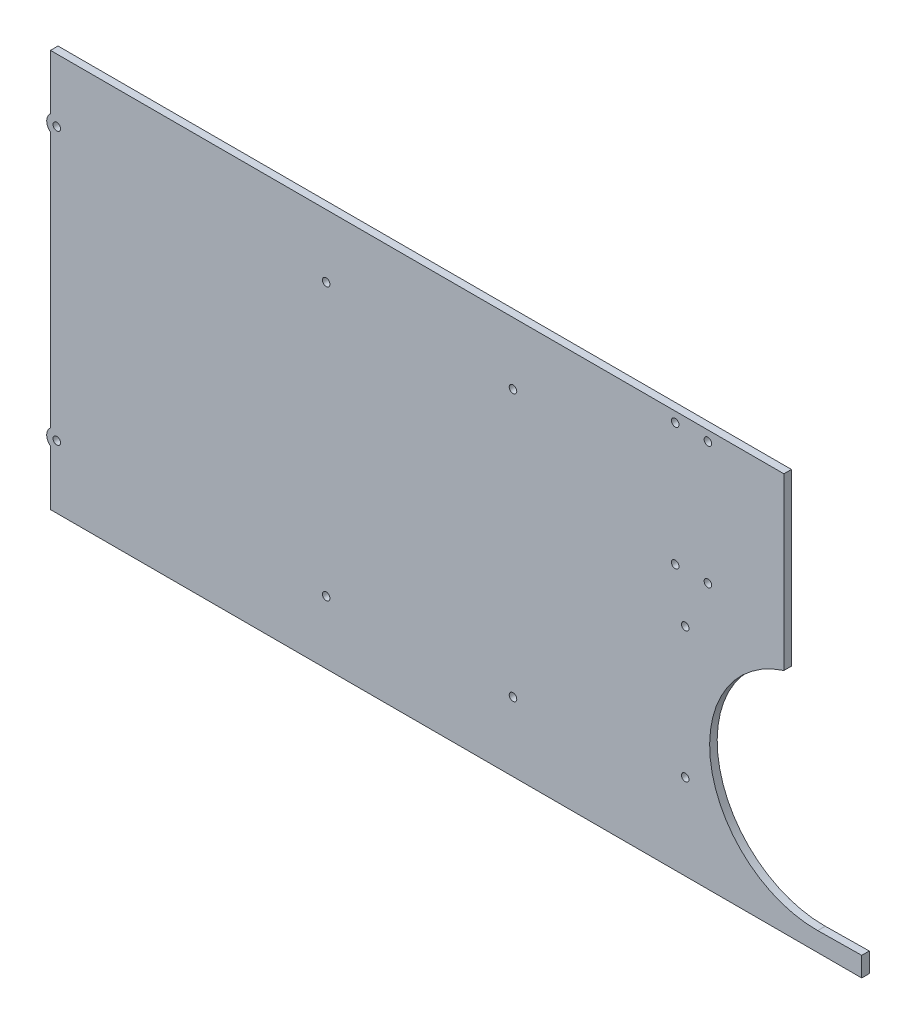
SolidWorks part; units mm, degrees
ref_plane "Front Plane" through (0, 0, 0) normal (0, 0, 1) x (1, 0, 0)
ref_plane "Top Plane" through (0, 0, 0) normal (0, 1, 0) x (1, 0, 0)
ref_plane "Right Plane" through (0, 0, 0) normal (1, 0, 0) x (0, 0, -1)
sketch "Sketch1" plane through (0, 0, 0) normal (0, 0, 1) x (1, 0, 0)
  line L1 (-254.8509, 60.2307) -> (36.7811, 60.2307)
  line L4 (36.7811, 60.2307) -> (36.7811, -7.5096)
  line L5 (-254.8509, 60.2307) -> (-254.8509, -97.9238)
  line L7 (23.7811, 60.2307) -> (33.7811, 60.2307) construction
  line L8 (36.7811, 82.5754) -> (36.7811, 0.2307) construction
  line L9 (82.6773, -97.9238) -> (-254.8509, -97.9238)
  line L11 (50.2242, -90.3422) -> (82.6773, -89.9238)
  line L12 (82.6773, -81.9238) -> (82.6773, -97.9238) construction
  line L13 (82.6773, -89.9238) -> (82.6773, -97.9238)
  circle A3 centre (49.6773, -47.9238) radius 42.4219 construction
  arc A4 (36.7811, -7.5096) -> (50.2242, -90.3422) centre (49.6773, -47.9238) ccw
  point P0 (0, 0)
  dimension "D1" = 337.5282
extrude "Boss-Extrude1" add sketch "Sketch1" along normal blind 3
sketch "Sketch3" plane through (0, 0, 3) normal (0, 0, 1) x (1, 0, 0)
  line L4 (-254.8509, -97.9238) -> (82.6773, -97.9238) construction
  line L5 (67.7284, -97.9238) -> (67.7284, -90.1165)
  line L6 (-254.8509, 60.2307) -> (-254.8509, -97.9238)
  line L7 (-254.8509, -97.9238) -> (82.6773, -97.9238)
  line L8 (82.6773, -97.9238) -> (82.6773, -89.9238)
  line L9 (82.6773, -89.9238) -> (50.2242, -90.3422)
  line L10 (36.7811, -7.5096) -> (36.7811, 60.2307)
  line L11 (36.7811, 60.2307) -> (-254.8509, 60.2307)
  line L13 (67.7284, -97.9238) -> (82.6773, -97.9238)
  line L14 (82.6773, -97.9238) -> (82.6773, -89.9238)
  line L16 (82.6773, -89.9238) -> (50.2242, -90.3422) construction
  line L17 (67.7284, -90.1165) -> (82.6773, -89.9238)
  arc A1 (36.7811, -7.5096) -> (50.2242, -90.3422) centre (49.6773, -47.9238) ccw
  dimension "D1" = 0
extrude "Cut-Extrude1" cut sketch "Sketch3" against normal blind 3
sketch "Sketch6" [suppressed] plane through (0, 0, 3) normal (0, 0, 1) x (1, 0, 0)
  line L0 (36.7811, -7.5096) -> (36.7811, 60.2307) construction
  line L1 (36.7811, 60.2307) -> (-97.7309, 60.2307) construction
  circle A1 centre (-1.4427, -11.9238) radius 2.675
  dimension "D1" = 5.35
  dimension "D2" = 38.2238
  dimension "D3" = 72.1546
ref_plane "Plane1" [suppressed] through (0, 0, 11.6832) normal (0, 0, 1) x (1, 0, 0)
sketch "Sketch7" [suppressed] plane through (0, 0, 11.6832) normal (0, 0, 1) x (1, 0, 0)
  line L0 (36.7811, -7.5096) -> (36.7811, 60.2307) construction
  line L1 (36.7811, 60.2307) -> (-97.7309, 60.2307) construction
  circle A1 centre (-1.4427, -11.9238) radius 1.5293
  dimension "D1" = 3.0586
  dimension "D2" = 38.2238
  dimension "D3" = 72.1546
ref_plane "Plane2" [suppressed] through (0, -37.9238, 0) normal (0, -1, 0) x (-1, 0, 0)
ref_plane "Plane3" [suppressed] through (-34.4427, 0, 0) normal (1, 0, 0) x (0, 0, -1)
sketch "Sketch10" plane through (0, 0, 3) normal (0, 0, 1) x (1, 0, 0)
  line L0 (36.7811, -7.5096) -> (36.7811, 60.2307) construction
  line L2 (36.7811, 60.2307) -> (-254.8509, 60.2307) construction
  line L3 (-2.4427, -11.9238) -> (-2.4427, -63.9238) construction
  circle A1 centre (-2.4427, -11.9238) radius 1.5
  circle A3 centre (-2.4427, -63.9238) radius 1.5
  dimension "D1" = 3
  dimension "D5" = 3
  dimension "D2" = 39.2238
  dimension "D3" = 72.1546
  dimension "D4" = 52
extrude "Cut-Extrude2" cut sketch "Sketch10" against normal blind 4
sketch "Sketch11" plane through (0, 0, 3) normal (0, 0, 1) x (1, 0, 0)
  line L0 (36.7811, 60.2307) -> (-254.8509, 60.2307) construction
  line L2 (-70.9427, 35.5075) -> (-70.9427, -70.4925) construction
  line L3 (36.7811, -7.5096) -> (36.7811, 60.2307) construction
  circle A1 centre (-70.9427, 35.5075) radius 1.5
  circle A2 centre (-70.9427, -70.4925) radius 1.5
  dimension "D1" = 3
  dimension "D5" = 3
  dimension "D2" = 24.7232
  dimension "D3" = 107.7238
  dimension "D4" = 106
extrude "Cut-Extrude3" cut sketch "Sketch11" against normal blind 4
sketch "Sketch12" plane through (0, 0, 3) normal (0, 0, 1) x (1, 0, 0)
  line L0 (36.7811, 60.2307) -> (-254.8509, 60.2307) construction
  line L1 (36.7811, -7.5096) -> (36.7811, 60.2307) construction
  line L2 (-13.7873, 31.8307) -> (12.1534, 31.8307) construction
  circle A0 centre (-6.4399, 56.2307) radius 1.5
  circle A1 centre (6.5601, 56.2307) radius 1.5
  circle A2 centre (6.5601, 7.4307) radius 1.5
  circle A3 centre (-6.4399, 7.4307) radius 1.5
  dimension "D1" = 3
  dimension "D4" = 3
  dimension "D2" = 4
  dimension "D3" = 30.221
  dimension "D5" = 13
  dimension "D6" = 24.4
extrude "Cut-Extrude4" cut sketch "Sketch12" against normal blind 10
sketch "Sketch13" plane through (0, 0, 3) normal (0, 0, 1) x (1, 0, 0)
  line L2 (-254.8509, -18.8465) -> (48.6711, -18.8465) construction
  line L6 (-254.8509, 60.2307) -> (-254.8509, -97.9238) construction
  line L7 (36.7811, 60.2307) -> (-254.8509, 60.2307) construction
  line L8 (36.7811, -7.5096) -> (36.7811, 60.2307) construction
  circle A0 centre (-145.2309, 35.2307) radius 1.5
  circle A1 centre (-145.2309, -72.9238) radius 1.5
  dimension "D1" = 3
  dimension "D2" = 182.012
  dimension "D3" = 25
extrude "Cut-Extrude5" cut sketch "Sketch13" against normal blind 10
sketch "Sketch14" [suppressed] plane through (0, 0, 3) normal (0, 0, 1) x (1, 0, 0)
  circle A0 centre (-120.2309, 45.2307) radius 4
  circle A1 centre (-120.2309, 45.2307) radius 1.5 construction
  circle A2 centre (-120.2309, 45.2307) radius 1.5
  circle A3 centre (-120.2309, -82.9238) radius 4
  circle A4 centre (-120.2309, -82.9238) radius 1.5 construction
  circle A5 centre (-120.2309, -82.9238) radius 1.5
  dimension "D1" = 8
  dimension "D2" = 8
extrude "Boss-Extrude2" [suppressed] add sketch "Sketch14" against normal blind 3
sketch "Sketch15" plane through (0, 0, 3) normal (0, 0, 1) x (1, 0, 0)
  line L0 (36.7811, -7.5096) -> (36.7811, 60.2307) construction
  line L7 (-254.8509, -97.9238) -> (67.7284, -97.9238) construction
  line L8 (-254.8509, 60.2307) -> (-254.8509, -97.9238) construction
  line L10 (-254.8509, -18.8465) -> (-153.7776, -18.8465) construction
  circle A0 centre (-252.3509, -72.9193) radius 1.5
  circle A1 centre (-252.3509, 35.2262) radius 1.5
  dimension "D1" = 3
  dimension "D2" = 25.0046
  dimension "D3" = 289.132
extrude "Cut-Extrude6" cut sketch "Sketch15" against normal blind 10
sketch "Sketch16" plane through (0, 0, 3) normal (0, 0, 1) x (1, 0, 0)
  circle A0 centre (-252.3509, -72.9193) radius 1.5 construction
  circle A1 centre (-252.3509, -72.9193) radius 1.5
  circle A2 centre (-252.3509, -72.9193) radius 4
  circle A3 centre (-252.3509, 35.2262) radius 1.5
  circle A4 centre (-252.3509, 35.2262) radius 4
  dimension "D1" = 8
  dimension "D2" = 8
extrude "Boss-Extrude3" add sketch "Sketch16" against normal blind 3
